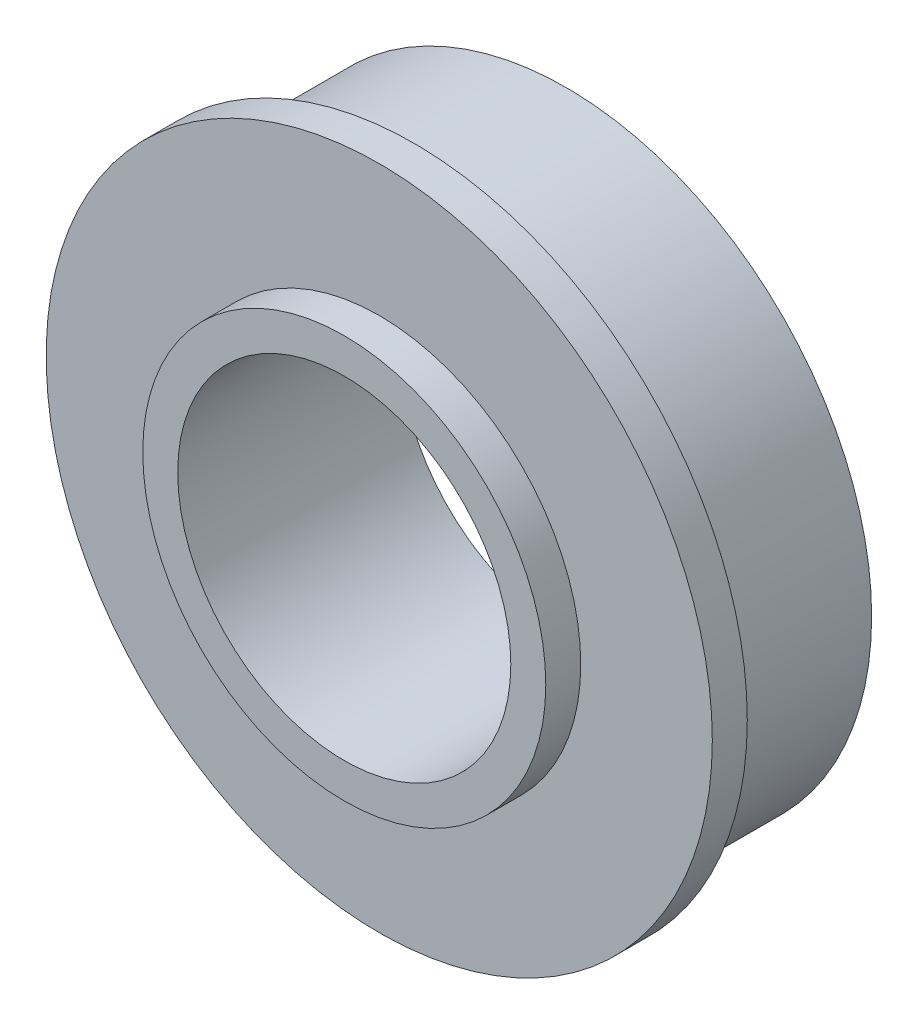
SolidWorks part; units mm, degrees
ref_plane "Front Plane" through (0, 0, 0) normal (0, 0, 1) x (1, 0, 0)
ref_plane "Top Plane" through (0, 0, 0) normal (0, 1, 0) x (1, 0, 0)
ref_plane "Right Plane" through (0, 0, 0) normal (1, 0, 0) x (0, 0, -1)
sketch "Sketch1" plane through (0, 0, 0) normal (0, 0, 1) x (1, 0, 0)
  circle A0 centre (0, 0) radius 9.525
  circle A1 centre (0, 0) radius 17.4625
  dimension "D1" = 19.05
  dimension "D2" = 34.925
extrude "Boss-Extrude1" add sketch "Sketch1" along normal blind 8.7
sketch "Sketch2" plane through (0, 0, 8.7) normal (0, 0, 1) x (1, 0, 0)
  circle A0 centre (0, 0) radius 19.05
  circle A1 centre (0, 0) radius 9.525
  circle A2 centre (0, 0) radius 9.525 construction
  dimension "D1" = 38.1
extrude "Boss-Extrude2" add sketch "Sketch2" along normal blind 2
sketch "Sketch3" plane through (0, 0, 10.7) normal (0, 0, 1) x (1, 0, 0)
  circle A0 centre (0, 0) radius 9.525
  circle A1 centre (0, 0) radius 11.525
  circle A2 centre (0, 0) radius 9.525 construction
  dimension "D1" = 2
extrude "Boss-Extrude3" add sketch "Sketch3" along normal blind 2
